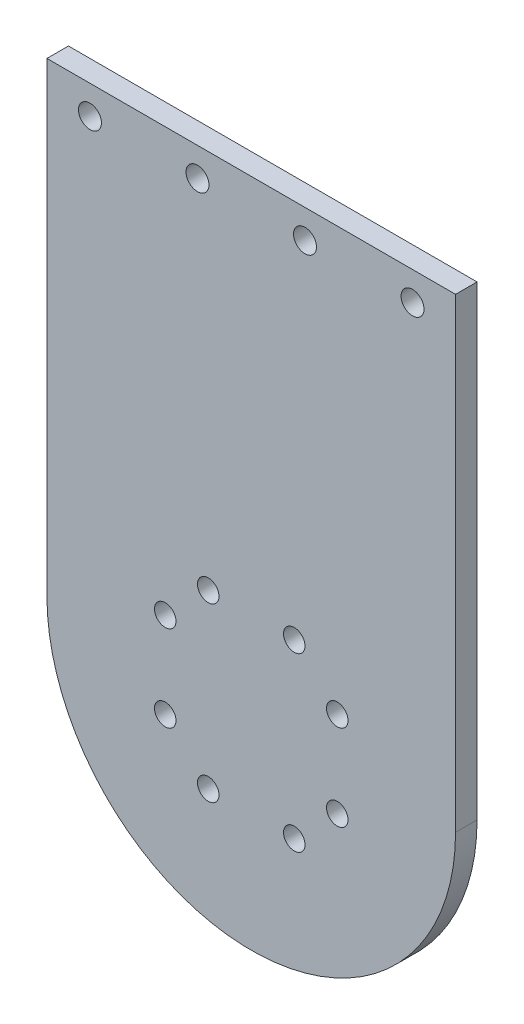
SolidWorks part; units mm, degrees
ref_plane "前基準面" through (0, 0, 0) normal (0, 0, 1) x (1, 0, 0)
ref_plane "上基準面" through (0, 0, 0) normal (0, 1, 0) x (1, 0, 0)
ref_plane "右基準面" through (0, 0, 0) normal (1, 0, 0) x (0, 0, -1)
sketch "草圖1" plane through (0, 0, 0) normal (0, 0, 1) x (1, 0, 0)
  line L0 (-28.5, 0) -> (28.5, 0)
  line L14 (28.5, 0) -> (28.5, -65)
  line L16 (-28.5, 0) -> (-28.5, -65)
  arc A2 (-28.5, -65) -> (28.5, -65) centre (0, -65) ccw
  dimension "D3" = 65
  dimension "D1" = 57
extrude "填料-伸長1" add sketch "草圖1" along normal blind 3
sketch "草圖3" plane through (0, 0, 3) normal (0, 0, 1) x (1, 0, 0)
  line L0 (-28.5, 0) -> (28.5, 0) construction
  line L1 (-28.5, 0) -> (-28.5, -65) construction
  circle A0 centre (-22.5, -4) radius 1.6
  dimension "D1" = 3.2
  dimension "D2" = 4
  dimension "D3" = 6
extrude "除料-伸長2" cut sketch "草圖3" against normal up to next
pattern_linear "直線複製排列1" count 4 spacing 15 along (1, 0, 0) of "除料-伸長2"
sketch "草圖2" plane through (0, 0, 3) normal (0, 0, 1) x (1, 0, 0)
  circle A1 centre (-6, -53) radius 1.5
  circle A2 centre (-12, -59) radius 1.5
  point P0 (0, -65)
  dimension "D1" = 6
  dimension "D2" = 3
  dimension "D4" = 6
  dimension "D3" = 12
  dimension "D5" = 12
extrude "除料-伸長1" cut sketch "草圖2" against normal up to next
pattern_circular "環狀複製排列1" count 4 over 360 about axis through (0, -65, 0) along (0, 0, 1) of "除料-伸長1"
